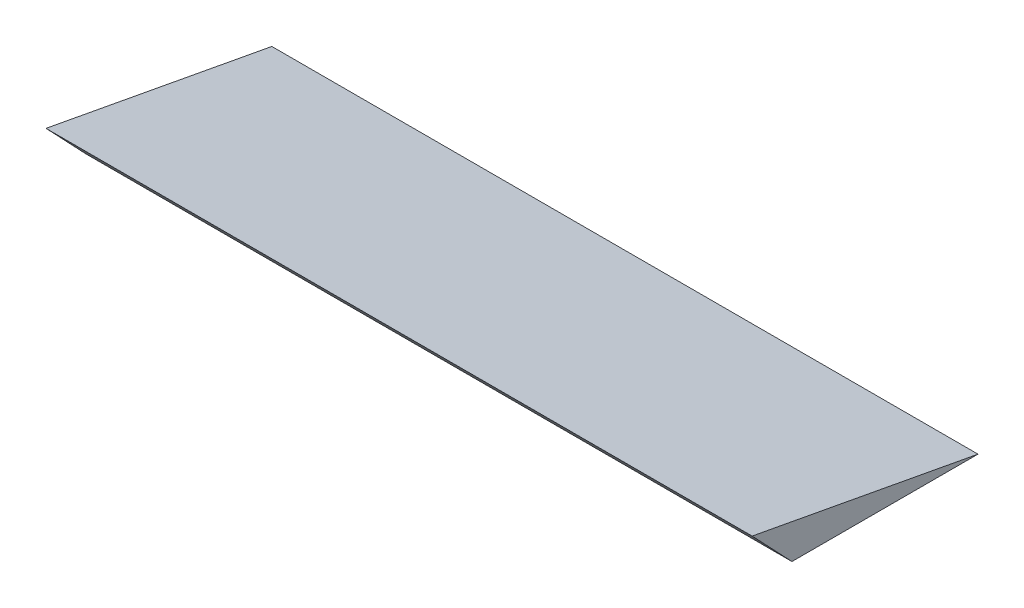
SolidWorks part; units mm, degrees
material "EPS 1.5lb"
ref_plane "Front Plane" through (0, 0, 0) normal (0, 0, 1) x (1, 0, 0)
ref_plane "Top Plane" through (0, 0, 0) normal (0, 1, 0) x (1, 0, 0)
ref_plane "Right Plane" through (0, 0, 0) normal (1, 0, 0) x (0, 0, -1)
sketch "Sketch1" plane through (0, 0, 0) normal (1, 0, 0) x (0, 0, -1)
  line L0 (-45.0555, 9.8913) -> (-27.2302, -8.9099)
  line L1 (-27.2302, -8.9099) -> (56.0818, -8.9099)
  line L2 (56.0818, -8.9099) -> (-45.0555, 9.8913)
  dimension "D1" = 25.908
  dimension "D2" = 102.87
  dimension "D3" = 83.312
extrude "Boss-Extrude1" add sketch "Sketch1" along normal blind 316.23
sketch "Sketch2" plane through (0, 0, 0) normal (1, 0, 0) x (0, 0, -1)
  line L0 (-45.0555, 9.8913) -> (-24.3286, 6.0382)
  line L1 (-43.0577, 9.5199) -> (-43.3275, 8.0687) construction
  line L2 (-24.3286, 6.0382) -> (-25.199, 1.3559)
  line L3 (-39.4802, 4.0107) -> (-25.199, 1.3559) construction
  line L4 (56.0818, -8.9099) -> (-45.0555, 9.8913) construction
  line L5 (-45.0555, 9.8913) -> (-39.4802, 4.0107)
  line L6 (-45.0555, 9.8913) -> (-27.2302, -8.9099) construction
  line L7 (-39.4802, 4.0107) -> (-25.199, 1.3559)
  dimension "D1" = 19.05
  dimension "D2" = 4.7625
  dimension "D3" = 2.032
extrude "Cut-Extrude1" [suppressed] cut sketch "Sketch2" along normal through all
ref_point "Point1" [suppressed]
ref_point "Point2" [suppressed]
ref_point "Point3" [suppressed]
ref_point "Point4" [suppressed]
ref_point "Point5" [suppressed]
ref_point "Point6" [suppressed]
ref_point "Point7" [suppressed]
ref_point "Point8" [suppressed]
ref_point "Point9" [suppressed]
ref_point "Point10" [suppressed]
ref_point "Point11" [suppressed]
ref_point "Point12" [suppressed]
ref_point "Point13" [suppressed]
ref_point "Point14" [suppressed]
ref_point "Point15" [suppressed]
ref_point "Point16" [suppressed]
ref_point "Point17" [suppressed]
ref_point "Point18" [suppressed]
ref_point "Point19" [suppressed]
ref_point "Point20" [suppressed]
